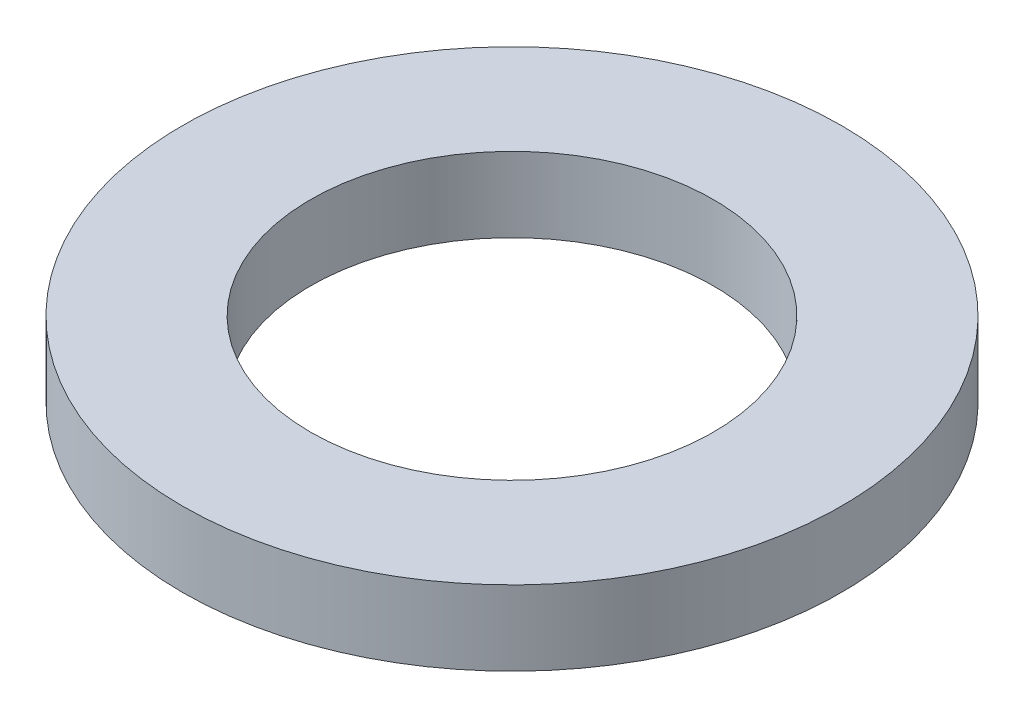
SolidWorks part; units mm, degrees
ref_plane "Front Plane" through (0, 0, 0) normal (0, 0, 1) x (1, 0, 0)
ref_plane "Top Plane" through (0, 0, 0) normal (0, 1, 0) x (1, 0, 0)
ref_plane "Right Plane" through (0, 0, 0) normal (1, 0, 0) x (0, 0, -1)
sketch "Sketch1" plane through (0, 0, 0) normal (0, 1, 0) x (1, 0, 0)
  circle A0 centre (0, 0) radius 9.5885
  circle A1 centre (0, 0) radius 15.6845
  dimension "D1" = 31.369
  dimension "D2" = 19.177
extrude "Boss-Extrude1" add sketch "Sketch1" along normal blind 3.5592
